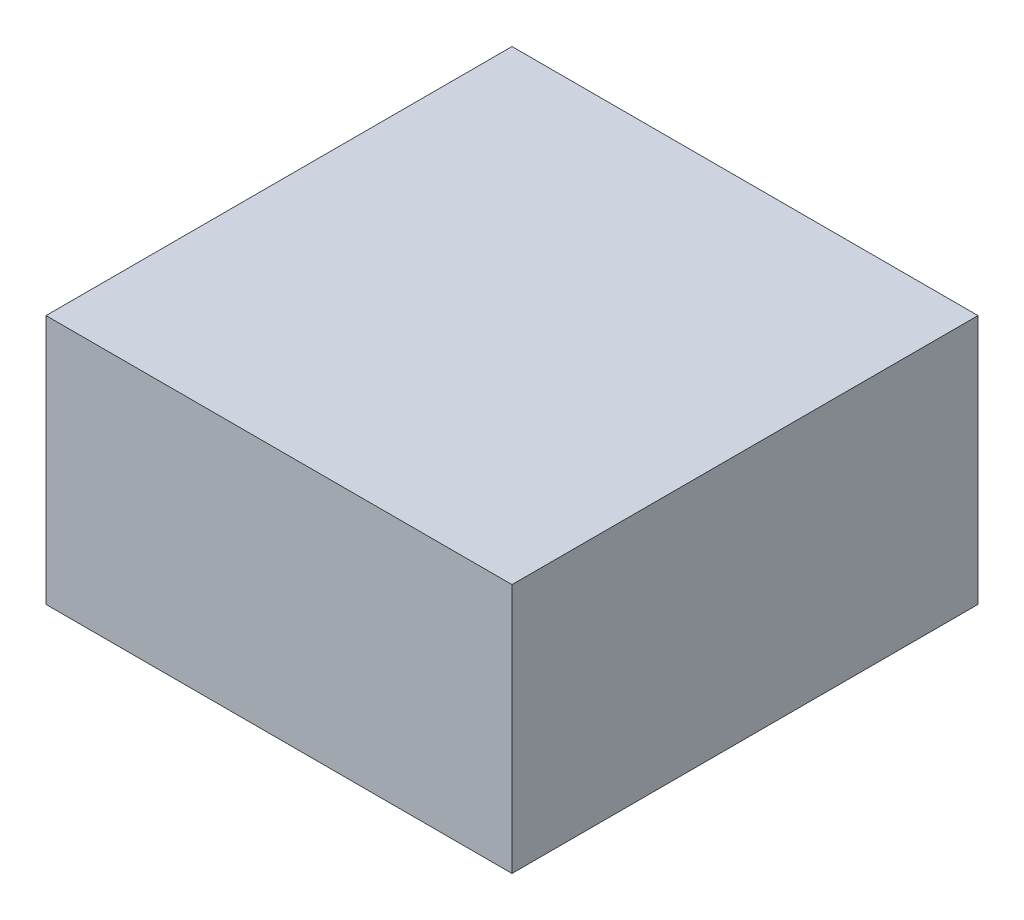
SolidWorks part; units mm, degrees
ref_plane "Front Plane" through (0, 0, 0) normal (0, 0, 1) x (1, 0, 0)
ref_plane "Top Plane" through (0, 0, 0) normal (0, 1, 0) x (1, 0, 0)
ref_plane "Right Plane" through (0, 0, 0) normal (1, 0, 0) x (0, 0, -1)
sketch "Sketch2" plane through (0, 0, 0) normal (0, 0, 1) x (1, 0, 0)
  line L1 (6.3738, 36.1182) -> (101.3738, 36.1182)
  line L2 (6.3738, 36.1182) -> (6.3738, -14.8818)
  line L3 (6.3738, -14.8818) -> (101.3738, -14.8818)
  line L4 (101.3738, 36.1182) -> (101.3738, -14.8818)
  dimension "D1" = 51
  dimension "D2" = 95
extrude "Boss-Extrude1" add sketch "Sketch2" along normal blind 95
